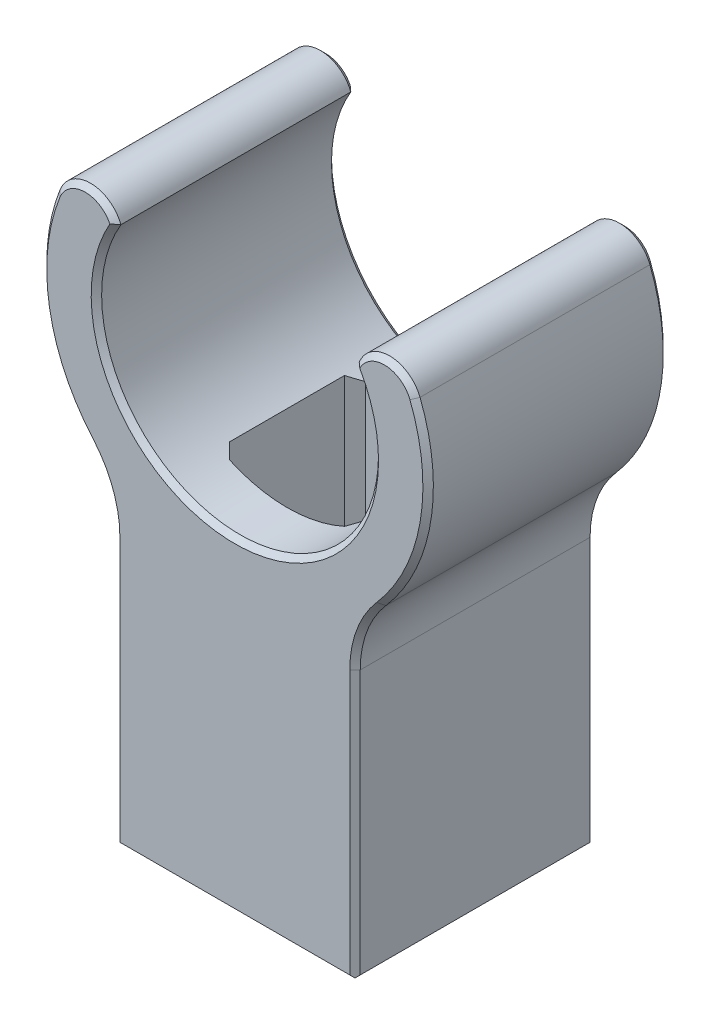
SolidWorks part; units mm, degrees
ref_plane "Front Plane" through (0, 0, 0) normal (0, 0, 1) x (1, 0, 0)
ref_plane "Top Plane" through (0, 0, 0) normal (0, 1, 0) x (1, 0, 0)
ref_plane "Right Plane" through (0, 0, 0) normal (1, 0, 0) x (0, 0, -1)
sketch "Sketch1" plane through (0, 0, 0) normal (0, 0, 1) x (1, 0, 0)
  line L6 (-28.7739, -13.25) -> (44.2672, -13.25) construction
  line L10 (-11.5, -14.4914) -> (-11.5, -44.4914)
  line L11 (-24.5505, 6.75) -> (34.718, 6.75) construction
  line L13 (-11.5, -44.4914) -> (11.5, -44.4914)
  line L14 (11.5, -14.4914) -> (11.5, -44.4914)
  arc A0 (-11.4018, 6.75) -> (11.4018, 6.75) centre (0, 0) ccw
  arc A1 (11.5, -14.4914) -> (17.2246, 6.75) centre (0, 0) ccw
  arc A6 (-17.2246, 6.75) -> (-11.5, -14.4914) centre (0, 0) ccw
  arc A7 (-17.2246, 6.75) -> (-11.4018, 6.75) centre (-14.3132, 5.6091) cw
  arc A8 (17.2246, 6.75) -> (11.4018, 6.75) centre (14.3132, 5.6091) ccw
  dimension "D1" = 26.5
  dimension "D2" = 37
  dimension "D3" = 23
  dimension "D4" = 30
  dimension "D5" = 20
extrude "Boss-Extrude1" add sketch "Sketch1" along normal blind 23
fillet "Fillet1" radius 10 2 edges at (-11.5, -14.4914, 11.5) (11.5, -14.4914, 11.5)
chamfer "Chamfer1" distance 0.5 angle 45 20 edges at (12.1341, -15.2039, 0) (18.2292, -3.1535, 0) (14.3132, 8.7361, 0) (0, -13.25, 0) (-14.3132, 8.7361, 0) (-18.2292, -3.1535, 0) (-12.1341, -15.2039, 0) (-11.5, -31.5998, 0) (0, -44.4914, 0) (11.5, -31.5998, 0) (0, -44.4914, 23) (-11.5, -31.5998, 23) (-12.1341, -15.2039, 23) (-18.2292, -3.1535, 23) (-14.3132, 8.7361, 23) (0, -13.25, 23) (14.3132, 8.7361, 23) (18.2292, -3.1535, 23) (12.1341, -15.2039, 23) (11.5, -31.5998, 23)
sketch "Sketch2" plane through (0, -44.4914, 0) normal (0, -1, 0) x (1, 0, 0)
  line L0 (-11, 23) -> (11, 23) construction
  line L1 (-6.5, 5) -> (6.5, 5)
  line L2 (-6.5, 5) -> (-6.5, 18)
  line L3 (-6.5, 18) -> (6.5, 18)
  line L4 (6.5, 5) -> (6.5, 18)
  line L5 (11.5, 22.5) -> (11.5, 0.5) construction
  line L6 (-11.5, 22.5) -> (-11.5, 0.5) construction
  line L7 (11, 0) -> (-11, 0) construction
  dimension "D1" = 5
  dimension "D2" = 5
  dimension "D3" = 5
  dimension "D4" = 5
extrude "Cut-Extrude1" cut sketch "Sketch2" against normal up to next
chamfer "Chamfer2" distance 1 angle 45 4 edges at (-6.5, -28.0187, 5) (6.5, -28.0187, 5) (6.5, -28.0187, 18) (-6.5, -28.0187, 18)
chamfer "Chamfer3" distance 0.5 angle 45 10 edges at (11.5, -44.4914, 11.5) (-11.5, -44.4914, 11.5) (-6, -44.4914, 5.5) (0, -44.4914, 5) (6, -44.4914, 5.5) (6.5, -44.4914, 11.5) (6, -44.4914, 17.5) (0, -44.4914, 18) (-6, -44.4914, 17.5) (-6.5, -44.4914, 11.5)
